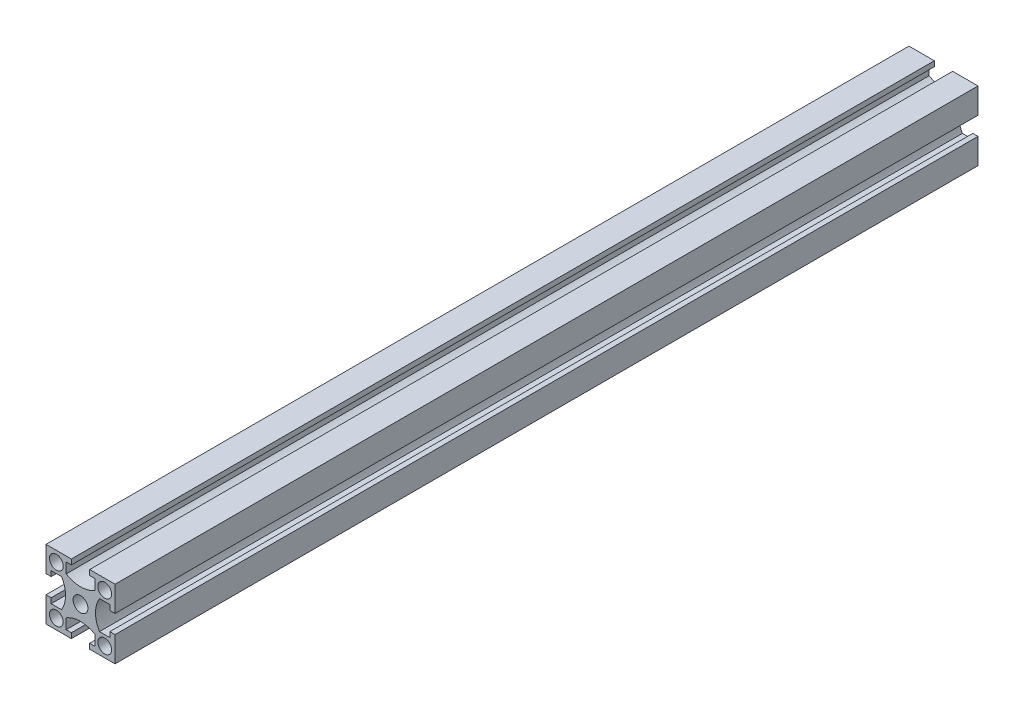
SolidWorks part; units mm, degrees
ref_plane "정면" through (0, 0, 0) normal (0, 0, 1) x (1, 0, 0)
ref_plane "윗면" through (0, 0, 0) normal (0, 1, 0) x (1, 0, 0)
ref_plane "우측면" through (0, 0, 0) normal (1, 0, 0) x (0, 0, -1)
sketch "스케치1" plane through (0, 0, 0) normal (0, 0, 1) x (1, 0, 0)
  line L1 (-10, 10) -> (10, 10)
  line L2 (-10, 10) -> (-10, -10)
  line L3 (-10, -10) -> (10, -10)
  line L4 (10, 10) -> (10, -10)
  line L5 (-10, 10) -> (10, -10) construction
  line L6 (-10, -10) -> (10, 10) construction
  point P0 (0, 0)
  dimension "D1" = 20
  dimension "D2" = 20
extrude "보스-돌출1" add sketch "스케치1" along normal blind 250
sketch "스케치2" plane through (0, 0, 250) normal (0, 0, 1) x (1, 0, 0)
  line L0 (-2.65, 10) -> (-2.65, 8.5)
  line L1 (10, 10) -> (-10, 10) construction
  line L2 (-2.65, 8.5) -> (-4.15, 8.5)
  line L3 (-4.15, 8.5) -> (-4.15, 5.5)
  line L4 (-2.65, 10) -> (2.65, 10)
  line L5 (2.65, 10) -> (2.65, 8.5)
  line L6 (2.65, 8.5) -> (4.15, 8.5)
  line L7 (4.15, 8.5) -> (4.15, 5.5)
  line L8 (10, 2.65) -> (8.5, 2.65)
  line L9 (8.5, 2.65) -> (8.5, 4.15)
  line L10 (8.5, 4.15) -> (5.5, 4.15)
  line L11 (10, 2.65) -> (10, -2.65)
  line L12 (10, -2.65) -> (8.5, -2.65)
  line L13 (8.5, -2.65) -> (8.5, -4.15)
  line L14 (8.5, -4.15) -> (5.5, -4.15)
  line L15 (2.65, -10) -> (2.65, -8.5)
  line L16 (2.65, -8.5) -> (4.15, -8.5)
  line L17 (4.15, -8.5) -> (4.15, -5.5)
  line L18 (2.65, -10) -> (-2.65, -10)
  line L19 (-2.65, -10) -> (-2.65, -8.5)
  line L20 (-2.65, -8.5) -> (-4.15, -8.5)
  line L21 (-4.15, -8.5) -> (-4.15, -5.5)
  line L22 (-10, -2.65) -> (-8.5, -2.65)
  line L23 (-8.5, -2.65) -> (-8.5, -4.15)
  line L24 (-8.5, -4.15) -> (-5.5, -4.15)
  line L25 (-10, -2.65) -> (-10, 2.65)
  line L26 (-10, 2.65) -> (-8.5, 2.65)
  line L27 (-8.5, 2.65) -> (-8.5, 4.15)
  line L28 (-8.5, 4.15) -> (-5.5, 4.15)
  arc A1 (-4.15, 5.5) -> (4.15, 5.5) centre (0, 12.3394) ccw
  arc A2 (5.5, 4.15) -> (5.5, -4.15) centre (12.3394, 0) ccw
  arc A3 (4.15, -5.5) -> (-4.15, -5.5) centre (0, -12.3394) ccw
  arc A4 (-5.5, -4.15) -> (-5.5, 4.15) centre (-12.3394, 0) ccw
  circle A5 centre (0, 0) radius 2.15
  circle A6 centre (-7, 7) radius 2
  circle A7 centre (7, 7) radius 2
  circle A8 centre (7, -7) radius 2
  circle A9 centre (-7, -7) radius 2
  point P4 (-2.65, 9.25)
  point P43 (0, 0)
  dimension "D2" = 1.5
  dimension "D8" = 4.3
  dimension "D9" = 4
  dimension "D10" = 4
  dimension "D11" = 4
  dimension "D12" = 4
  dimension "D21" = 8
  dimension "D1" = 5.3
  dimension "D3" = 8.3
  dimension "D4" = 4.15
  dimension "D5" = 2.65
  dimension "D6" = 4
  dimension "D7" = 3
  dimension "D13" = 14
  dimension "D14" = 7
  dimension "D15" = 7
  dimension "D16" = 7
  dimension "D17" = 14
  dimension "D18" = 7
  dimension "D19" = 7
  dimension "D20" = 7
extrude "컷-돌출1" cut sketch "스케치2" against normal blind 300
